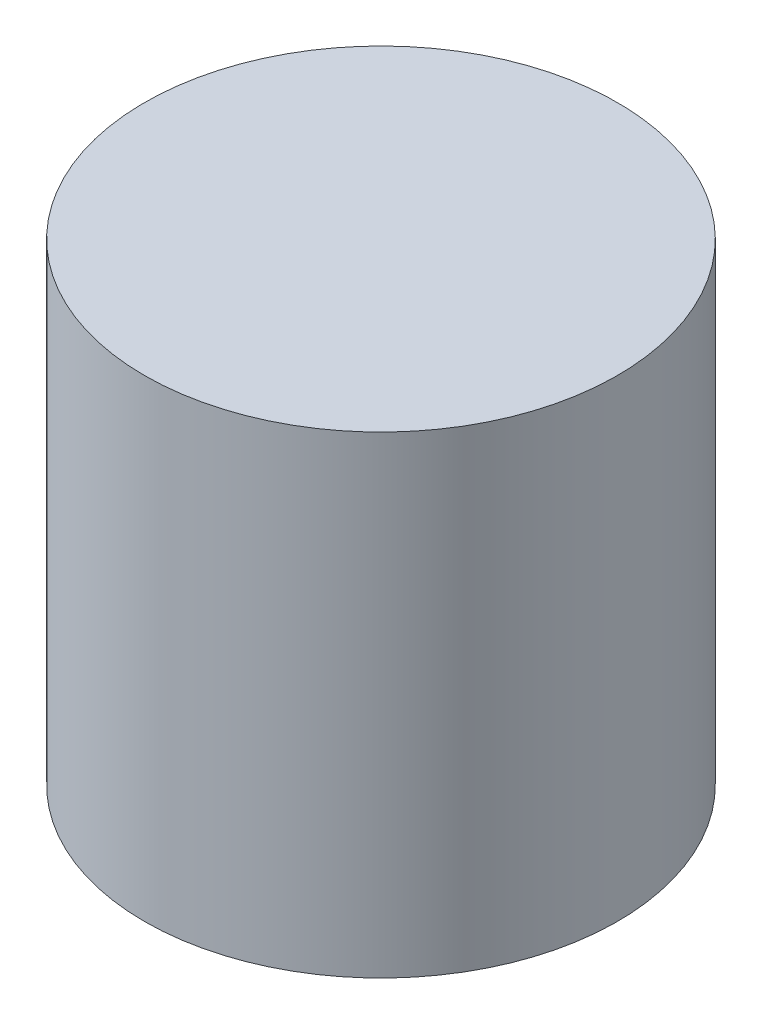
SolidWorks part; units mm, degrees
ref_plane "Front Plane" through (0, 0, 0) normal (0, 0, 1) x (1, 0, 0)
ref_plane "Top Plane" through (0, 0, 0) normal (0, 1, 0) x (1, 0, 0)
ref_plane "Right Plane" through (0, 0, 0) normal (1, 0, 0) x (0, 0, -1)
sketch "Sketch1" plane through (0, 0, 0) normal (0, 1, 0) x (1, 0, 0)
  circle A0 centre (0, 0) radius 3.5
  dimension "D1" = 7
extrude "Boss-Extrude1" add sketch "Sketch1" along normal blind 7
